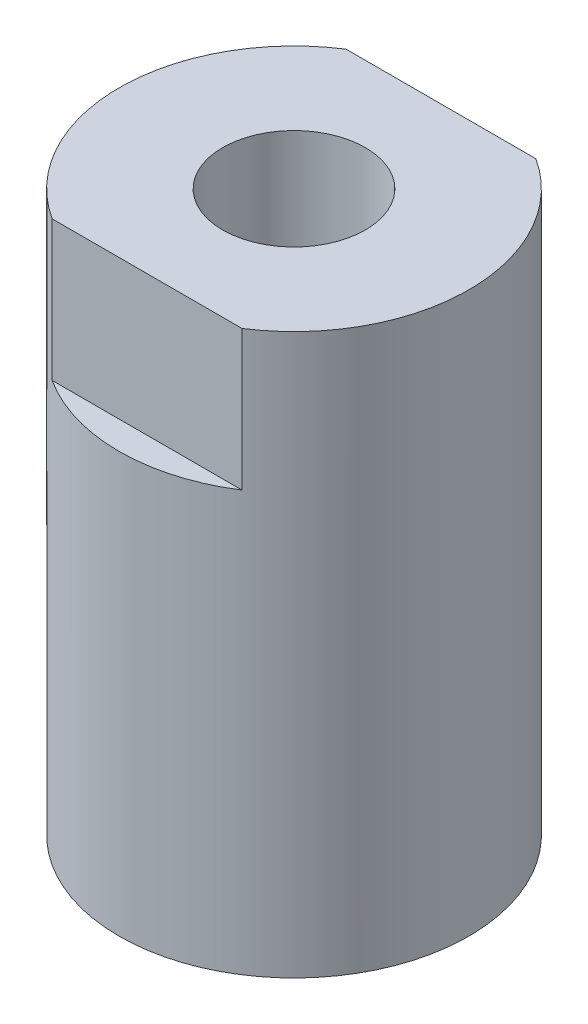
SolidWorks part; units mm, degrees
ref_plane "前视基准面" through (0, 0, 0) normal (0, 0, 1) x (1, 0, 0)
ref_plane "上视基准面" through (0, 0, 0) normal (0, 1, 0) x (1, 0, 0)
ref_plane "右视基准面" through (0, 0, 0) normal (1, 0, 0) x (0, 0, -1)
sketch "草图1" plane through (0, 0, 0) normal (0, 1, 0) x (1, 0, 0)
  circle A0 centre (0, 0) radius 12.5
  dimension "D1" = 25
extrude "凸台-拉伸1" add sketch "草图1" along normal blind 40
sketch "草图2" plane through (0, 40, 0) normal (0, 1, 0) x (1, 0, 0)
  line L0 (-18, -13.5) -> (-18, 13.5)
  line L1 (15, -10.5) -> (-15, -10.5)
  line L2 (15, -10.5) -> (15, 10.5)
  line L3 (15, 10.5) -> (-15, 10.5)
  line L4 (-15, -10.5) -> (-15, 10.5)
  line L5 (15, -10.5) -> (-15, 10.5) construction
  line L6 (15, 10.5) -> (-15, -10.5) construction
  line L7 (18, 13.5) -> (-18, 13.5)
  line L8 (18, -13.5) -> (18, 13.5)
  line L9 (18, -13.5) -> (-18, -13.5)
  point P0 (0, 0)
  dimension "D1" = 21
  dimension "D2" = 30
  dimension "D3" = 3
extrude "切除-拉伸1" cut sketch "草图2" against normal blind 10
hole_wizard "M12 螺纹孔1" positions "草图3" profile "草图4" tap size "M12" standard "GB" end condition through all
sketch "草图3" plane through (0, 40, 0) normal (0, 1, 0) x (1, 0, 0)
  point P0 (0, 0)
sketch "草图4" plane through (0, 40, 0) normal (1, 0, 0) x (0, 0, 1)
  line L0 (0, 0) -> (0, 40)
  line L1 (0, 40) -> (5.1, 40)
  line L2 (5.1, 40) -> (5.1, 0)
  line L5 (5.1, 0) -> (0, 0)
  line L11 (0, -6.35) -> (0, 107.95) construction
  dimension "通孔螺纹孔钻头直径" = 10.2
  dimension "通孔螺纹孔钻头深度" = 40
cosmetic thread "孔螺蚊线1" parameters "D2"=12
